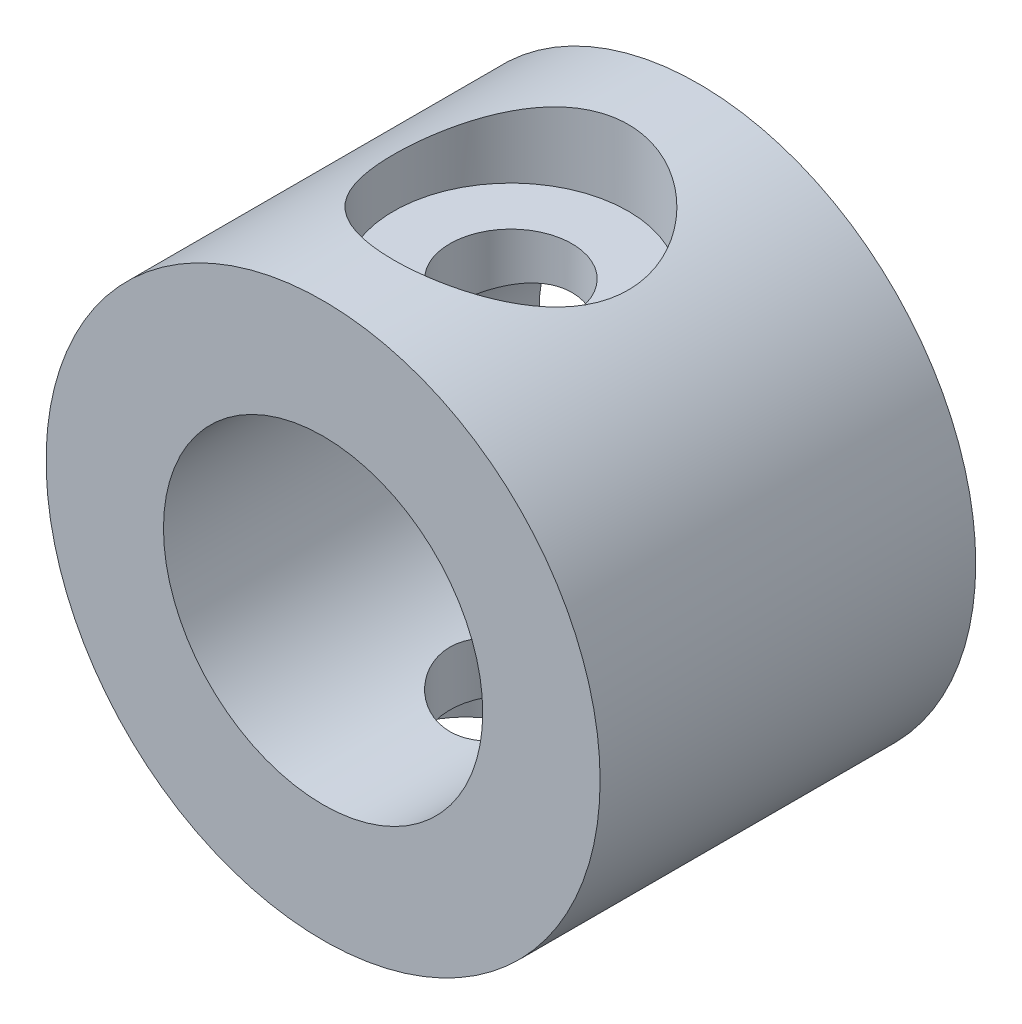
SolidWorks part; units mm, degrees
ref_plane "정면" through (0, 0, 0) normal (0, 0, 1) x (1, 0, 0)
ref_plane "윗면" through (0, 0, 0) normal (0, 1, 0) x (1, 0, 0)
ref_plane "우측면" through (0, 0, 0) normal (1, 0, 0) x (0, 0, -1)
sketch "스케치1" plane through (0, 0, 0) normal (0, 0, 1) x (1, 0, 0)
  circle A0 centre (0, 0) radius 3.4
  circle A1 centre (0, 0) radius 5.9
  dimension "D1" = 6.8
  dimension "D2" = 11.8
extrude "보스-돌출1" add sketch "스케치1" along normal blind 8
ref_plane "평면1" through (0, 5.9, 0) normal (0, 1, 0) x (1, 0, 0)
sketch "스케치2" plane through (0, 5.9, 0) normal (0, 1, 0) x (1, 0, 0)
  line L0 (-5.9, -8) -> (-5.9, 0) construction
  line L1 (-5.9, 0) -> (5.9, 0) construction
  point P4 (0, -4)
  dimension "D1" = 4
  dimension "D2" = 5.9
hole_wizard "M2 남비 머리 나사용 카운터보어3" positions "스케치5" profile "스케치6" counterbore size "M2" standard "ISO"
sketch "스케치5" plane through (0, 5.9, 0) normal (0, 1, 0) x (1, 0, 0)
  point P0 (0, -4)
sketch "스케치6" plane through (0, 5.9, 4) normal (1, 0, 0) x (0, 0, 1)
  line L0 (0, 0) -> (0, 5.7811)
  line L1 (0, 5.7811) -> (1.3, 5)
  line L2 (1.3, 5) -> (1.3, 1.6)
  line L3 (1.3, 1.6) -> (2.5, 1.6)
  line L4 (2.5, 1.6) -> (2.5, 0)
  line L5 (2.5, 0) -> (0, 0)
  line L10 (0, 5.7811) -> (-1.3, 5) construction
  line L11 (0, -6.35) -> (0, 107.95) construction
  dimension "구멍 지름" = 2.6
  dimension "구멍 깊이" = 5
  dimension "카운터보어 지름" = 5
  dimension "카운터보어 깊이" = 1.6
  dimension "드릴 각도" = 118
pattern_circular "원형 패턴1" count 2 over 360 about axis through (0, 0, 8) along (0, 0, 1) of "M2 남비 머리 나사용 카운터보어3"
